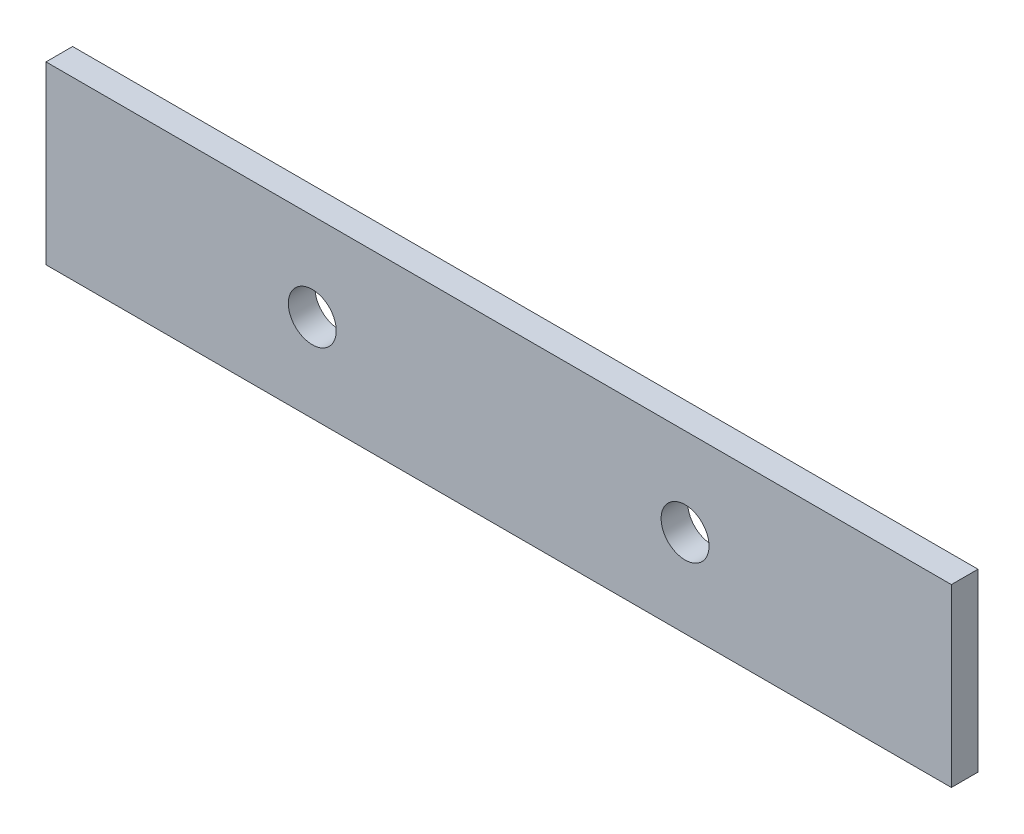
SolidWorks part; units mm, degrees
ref_plane "Front Plane" through (0, 0, 0) normal (0, 0, 1) x (1, 0, 0)
ref_plane "Top Plane" through (0, 0, 0) normal (0, 1, 0) x (1, 0, 0)
ref_plane "Right Plane" through (0, 0, 0) normal (1, 0, 0) x (0, 0, -1)
sketch "Sketch1" plane through (0, 0, 0) normal (0, 1, 0) x (1, 0, 0)
  line L1 (0, 0) -> (170, 0)
  line L2 (0, 0) -> (0, 5)
  line L3 (0, 5) -> (170, 5)
  line L4 (170, 0) -> (170, 5)
  dimension "D1" = 170
  dimension "D2" = 5
extrude "Boss-Extrude1" add sketch "Sketch1" along normal blind 33
sketch "Sketch2" plane through (0, 0, 0) normal (0, 0, 1) x (1, 0, 0)
  line L0 (0, 16.5) -> (170, 16.5) construction
  line L1 (0, 33) -> (0, 0) construction
  line L2 (170, 33) -> (170, 0) construction
  line L3 (85, 33) -> (85, 0) construction
  line L4 (0, 33) -> (170, 33) construction
  line L5 (0, 0) -> (170, 0) construction
  line L6 (120, 42.2675) -> (120, -15.4066) construction
  line L7 (50, 42.2675) -> (50, -15.4066) construction
  circle A0 centre (50, 16.5) radius 4.5
  circle A1 centre (120, 16.5) radius 4.5
  dimension "D1" = 50
extrude "Cut-Extrude1" cut sketch "Sketch2" against normal blind 10
